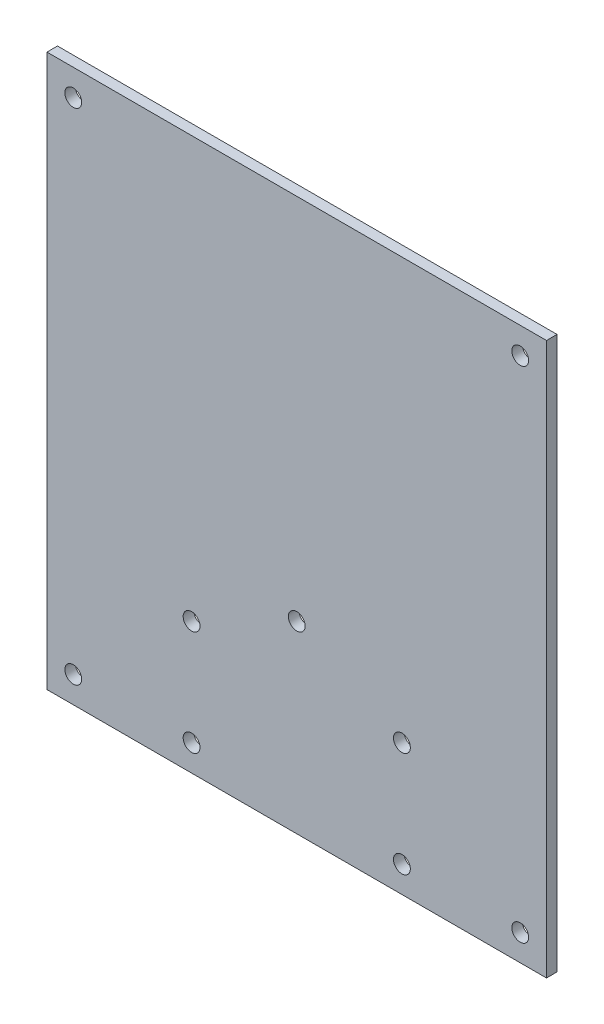
SolidWorks part; units mm, degrees
ref_plane "前基準面" through (0, 0, 0) normal (0, 0, 1) x (1, 0, 0)
ref_plane "上基準面" through (0, 0, 0) normal (0, 1, 0) x (1, 0, 0)
ref_plane "右基準面" through (0, 0, 0) normal (1, 0, 0) x (0, 0, -1)
sketch "草圖1" plane through (0, 0, 0) normal (0, 0, 1) x (1, 0, 0)
  line L0 (-47.5, 0) -> (47.5, 0)
  line L1 (-47.5, 0) -> (-47.5, 105)
  line L2 (-47.5, 105) -> (47.5, 105)
  line L3 (47.5, 105) -> (47.5, 0)
  line L4 (47.5, 0) -> (51.5, 0)
  line L6 (-25, 30) -> (25, 30)
  line L7 (-25, 30) -> (-25, 0)
  line L8 (25, 30) -> (25, 0)
  circle A0 centre (42.5, 5) radius 1.6
  circle A1 centre (42.5, 100) radius 1.6
  circle A2 centre (-42.5, 5) radius 1.6
  circle A3 centre (-42.5, 100) radius 1.6
  circle A5 centre (0, 35) radius 1.6
  circle A6 centre (-20, 25) radius 1.6
  circle A7 centre (20, 25) radius 1.6
  circle A8 centre (20, 5) radius 1.6
  circle A9 centre (-20, 5) radius 1.6
  point P4 (0, 0)
  point P9 (0, 0)
  point P13 (0, 0)
  point P22 (0, 30)
  point P26 (0, 0)
  point P27 (0, 0)
  point P36 (7.1875, 34.4865)
  dimension "D1" = 105
  dimension "D3" = 3.2
  dimension "D4" = 3.2
  dimension "D5" = 3.2
  dimension "D6" = 3.2
  dimension "D7" = 30
  dimension "D16" = 3.2
  dimension "D17" = 3.2
  dimension "D18" = 3.2
  dimension "D19" = 3.2
  dimension "D22" = 3.2
  dimension "D2" = 95
  dimension "D8" = 85
  dimension "D9" = 5
  dimension "D10" = 5
  dimension "D11" = 95
  dimension "D12" = 50
  dimension "D13" = 22.5
  dimension "D14" = 5
  dimension "D15" = 5
  dimension "D20" = 40
  dimension "D21" = 20
  dimension "D23" = 47.5
  dimension "D24" = 35
extrude "填料-伸長3" add sketch "草圖1" along normal blind 2 contours L6 L8 L0 L3 L2 L1 L7 A5 A3 A1 A0 A2 | L8 L6 L7 L0 A7 A6 A8 A9
